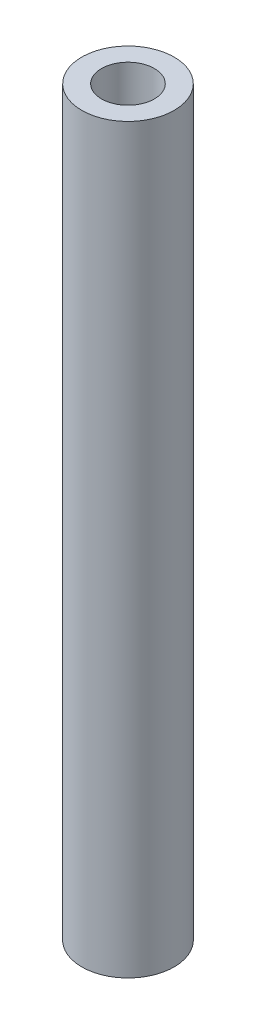
SolidWorks part; units mm, degrees
material "6061 合金"
ref_plane "前视基准面" through (0, 0, 0) normal (0, 0, 1) x (1, 0, 0)
ref_plane "上视基准面" through (0, 0, 0) normal (0, 1, 0) x (1, 0, 0)
ref_plane "右视基准面" through (0, 0, 0) normal (1, 0, 0) x (0, 0, -1)
sketch "草图1" plane through (0, 0, 0) normal (0, 1, 0) x (1, 0, 0)
  circle A0 centre (0, 0) radius 2
  circle A1 centre (0, 0) radius 3.5
extrude "凸台-拉伸1" add sketch "草图1" along normal mid plane 56.2
